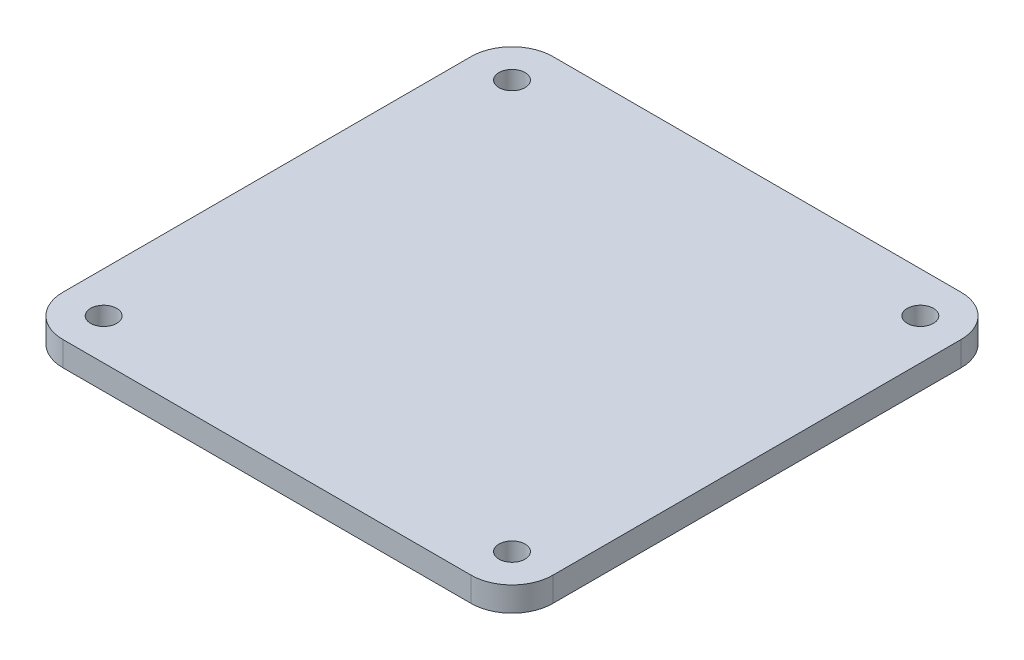
SolidWorks part; units mm, degrees
material "Acrylic (Medium-high impact)"
ref_plane "Front Plane" through (0, 0, 0) normal (0, 0, 1) x (1, 0, 0)
ref_plane "Top Plane" through (0, 0, 0) normal (0, 1, 0) x (1, 0, 0)
ref_plane "Right Plane" through (0, 0, 0) normal (1, 0, 0) x (0, 0, -1)
other "Configuration Table"
sketch "Sketch1" plane through (0, 4.2575, 0) normal (0, 1, 0) x (1, 0, 0)
  line L4 (-30, 25) -> (-30, -25)
  line L5 (-25, -30) -> (25, -30)
  line L6 (30, -25) -> (30, 25)
  line L7 (25, 30) -> (-25, 30)
  line L8 (-30, 25) -> (-30, -25)
  line L9 (-25, -30) -> (25, -30)
  line L10 (30, -25) -> (30, 25)
  line L11 (25, 30) -> (-25, 30)
  circle A1 centre (25, 25) radius 1.6
  circle A2 centre (25, 25) radius 1.6
  circle A3 centre (-25, 25) radius 1.6
  circle A4 centre (-25, 25) radius 1.6
  circle A5 centre (-25, -25) radius 1.6
  circle A6 centre (-25, -25) radius 1.6
  circle A7 centre (25, -25) radius 1.6
  circle A8 centre (25, -25) radius 1.6
  arc A12 (-30, -25) -> (-25, -30) centre (-25, -25) ccw
  arc A13 (25, -30) -> (30, -25) centre (25, -25) ccw
  arc A14 (30, 25) -> (25, 30) centre (25, 25) ccw
  arc A15 (-25, 30) -> (-30, 25) centre (-25, 25) ccw
  arc A16 (-30, -25) -> (-25, -30) centre (-25, -25) ccw
  arc A17 (25, -30) -> (30, -25) centre (25, -25) ccw
  arc A18 (30, 25) -> (25, 30) centre (25, 25) ccw
  arc A19 (-25, 30) -> (-30, 25) centre (-25, 25) ccw
  dimension "D1" = 0
  dimension "D2" = 0
  dimension "D3" = 0
  dimension "D4" = 0
  dimension "D5" = 0
extrude "Boss-Extrude1" add sketch "Sketch1" along normal blind 3
